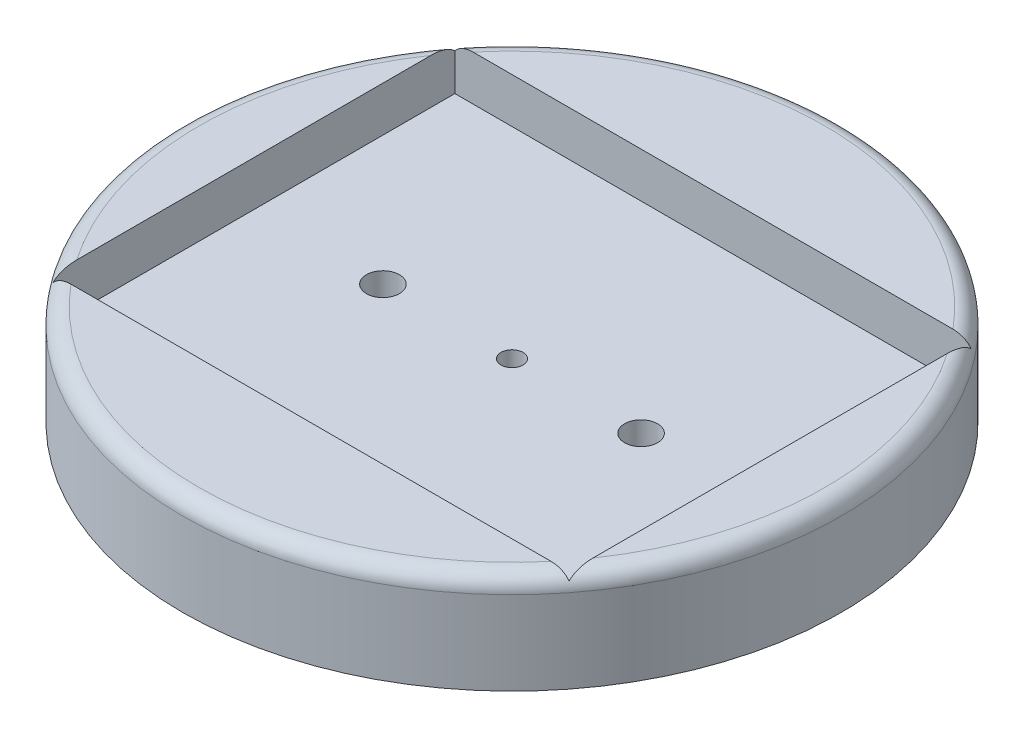
SolidWorks part; units mm, degrees
ref_plane "Front Plane" through (0, 0, 0) normal (0, 0, 1) x (1, 0, 0)
ref_plane "Top Plane" through (0, 0, 0) normal (0, 1, 0) x (1, 0, 0)
ref_plane "Right Plane" through (0, 0, 0) normal (1, 0, 0) x (0, 0, -1)
sketch "Sketch1" plane through (0, 0, 0) normal (0, 1, 0) x (1, 0, 0)
  circle A0 centre (0, 0) radius 30
  dimension "D1" = 60
extrude "Boss-Extrude1" add sketch "Sketch1" along normal blind 9.1
fillet "Fillet1" radius 1.5 1 edges at (0, 9.1, 30)
sketch "Sketch2" plane through (0, 9.1, 0) normal (0, 1, 0) x (1, 0, 0)
  line L1 (-23.5, -18.3) -> (23.5, -18.3)
  line L2 (-23.5, -18.3) -> (-23.5, 18.3)
  line L3 (-23.5, 18.3) -> (23.5, 18.3)
  line L4 (23.5, -18.3) -> (23.5, 18.3)
  line L5 (-23.5, -18.3) -> (23.5, 18.3) construction
  line L6 (-23.5, 18.3) -> (23.5, -18.3) construction
  point P0 (0, 0)
  dimension "D1" = 47
  dimension "D2" = 36.6
extrude "Cut-Extrude1" cut sketch "Sketch2" against normal blind 4.1
sketch "Sketch3" plane through (0, 5, 0) normal (0, 1, 0) x (1, 0, 0)
  line L0 (0, 18.3) -> (0, -18.3) construction
  line L4 (23.5, -18.3) -> (23.5, 18.3)
  line L5 (23.5, 18.3) -> (-23.5, 18.3)
  line L6 (-23.5, 18.3) -> (-23.5, -18.3)
  line L7 (-23.5, -18.3) -> (23.5, -18.3)
  line L8 (23.5, -18.3) -> (23.5, 18.3) construction
  line L9 (23.5, 18.3) -> (-23.5, 18.3) construction
  line L10 (-23.5, 18.3) -> (-23.5, -18.3) construction
  line L11 (-23.5, -18.3) -> (23.5, -18.3) construction
  circle A0 centre (11.75, 0) radius 1.5
  circle A1 centre (-11.75, 0) radius 1.5
  dimension "D4" = 3
  dimension "D2" = 11.75
  dimension "D3" = 18.3
  dimension "D1" = 0
extrude "Cut-Extrude2" cut sketch "Sketch3" against normal through all
sketch "Sketch4" plane through (0, 0, 0) normal (0, -1, 0) x (1, 0, 0)
  line L0 (0, 11.8) -> (0, 3.75) construction
  line L1 (-2.3891, 14.4282) -> (-3.733, 0.3565)
  line L2 (2.3891, 14.4282) -> (3.733, 0.3565)
  line L3 (3.733, -0.3565) -> (2.3891, -14.4282)
  line L4 (-3.733, -0.3565) -> (-2.3891, -14.4282)
  line L5 (0, -3.75) -> (0, -11.8) construction
  arc A0 (-3.733, 0.3565) -> (-3.733, -0.3565) centre (0, 0) ccw
  arc A1 (-2.3891, -14.4282) -> (2.3891, -14.4282) centre (0, -14.2) ccw
  arc A2 (2.3891, 14.4282) -> (-2.3891, 14.4282) centre (0, 14.2) ccw
  arc A3 (3.733, -0.3565) -> (3.733, 0.3565) centre (0, 0) ccw
  dimension "D2" = 7.5
  dimension "D3" = 4.8
  dimension "D4" = 4.8
  dimension "D1" = 28.4
extrude "Cut-Extrude3" cut sketch "Sketch4" against normal blind 3
sketch "Sketch5" plane through (0, 3, 0) normal (0, -1, 0) x (1, 0, 0)
  circle A0 centre (0, 0) radius 1
  dimension "D1" = 2
extrude "Cut-Extrude4" cut sketch "Sketch5" against normal through all
